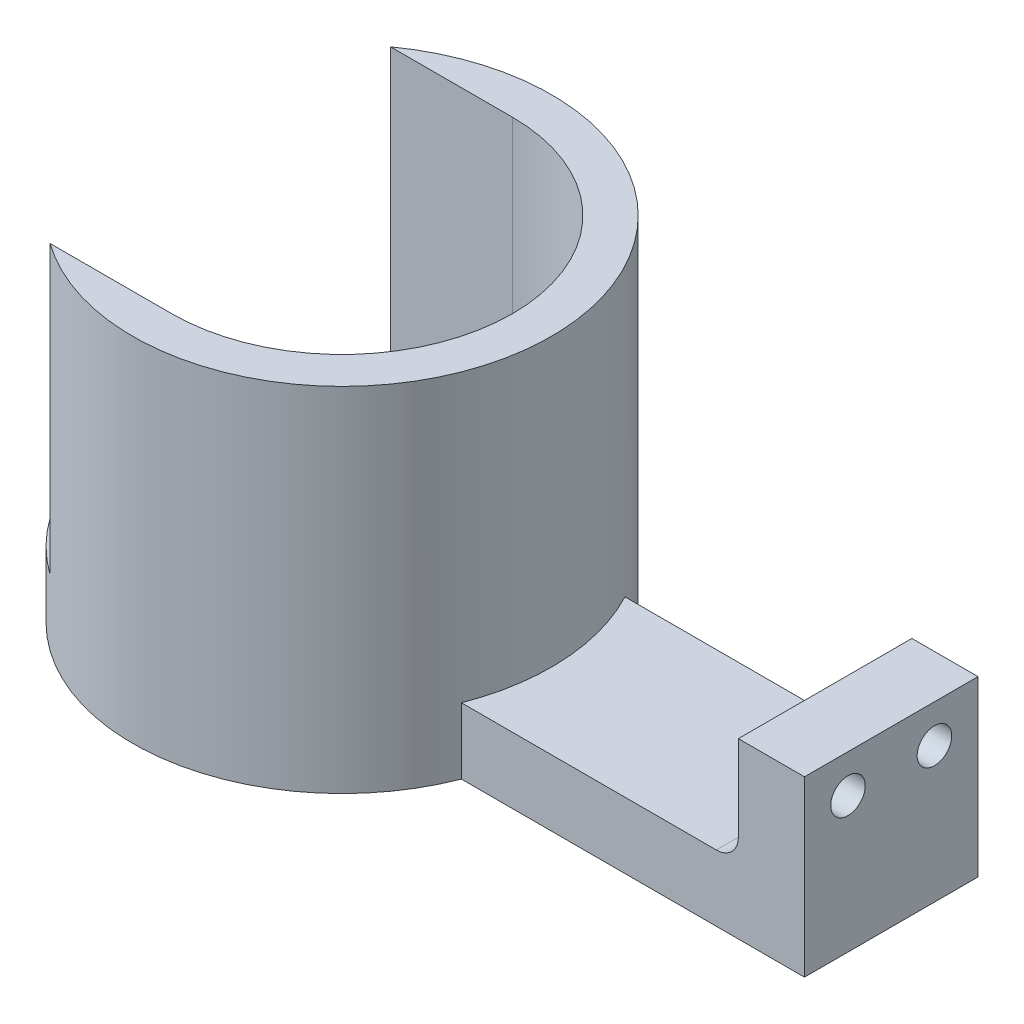
SolidWorks part; units mm, degrees
ref_plane "Front Plane" through (0, 0, 0) normal (0, 0, 1) x (1, 0, 0)
ref_plane "Top Plane" through (0, 0, 0) normal (0, 1, 0) x (1, 0, 0)
ref_plane "Right Plane" through (0, 0, 0) normal (1, 0, 0) x (0, 0, -1)
sketch "Sketch1" plane through (0, 0, 0) normal (0, 1, 0) x (1, 0, 0)
  line L1 (42.6873, 22.5127) -> (124.0573, 22.5127)
  line L2 (42.6873, 22.5127) -> (42.6873, -17.4873)
  line L3 (42.6873, -17.4873) -> (124.0573, -17.4873)
  line L4 (124.0573, 22.5127) -> (124.0573, -17.4873)
  circle A0 centre (0, 0) radius 26.5621
  circle A2 centre (0, 0) radius 48.26
  dimension "D1" = 53.1241
  dimension "D4" = 96.52
  dimension "D2" = 81.37
  dimension "D3" = 40
extrude "Boss-Extrude2" add sketch "Sketch1" along normal blind 15.24 contours L2 A2 A0 | A2 L3 L4 L1 | L2 A2
sketch "Sketch2" plane through (0, 0, -22.5127) normal (0, 0, -1) x (-1, 0, 0)
  line L1 (-124.0573, 15.24) -> (-108.8173, 15.24)
  line L2 (-124.0573, 15.24) -> (-124.0573, 40)
  line L3 (-124.0573, 40) -> (-108.8173, 40)
  line L4 (-108.8173, 15.24) -> (-108.8173, 40)
  dimension "D1" = 15.24
extrude "Boss-Extrude3" add sketch "Sketch2" against normal up to surface (40 mm away) up to face at (84.5188, 7.62, 17.4873)
sketch "Sketch3" plane through (108.8173, 0, 0) normal (-1, 0, 0) x (0, 0, 1)
  line L0 (-22.5127, 15.24) -> (-22.5127, 40) construction
  line L1 (17.4873, 40) -> (-22.5127, 40) construction
  line L2 (17.4873, 40) -> (17.4873, 15.24) construction
  circle A0 centre (7.4492, 31.2218) radius 3.9774
  circle A1 centre (-12.4746, 31.2218) radius 3.9851
  dimension "D1" = 7.9547
  dimension "D2" = 7.9703
  dimension "D3" = 10.0381
  dimension "D4" = 8.7782
  dimension "D5" = 8.7782
  dimension "D6" = 10.0381
extrude "Cut-Extrude1" cut sketch "Sketch3" against normal through all
fillet "Fillet1" radius 5.08 1 edges at (108.8173, 15.24, -2.5127)
sketch "Sketch5" plane through (0, 15.24, 0) normal (0, 1, 0) x (1, 0, 0)
  line L0 (0, -39.2481) -> (-28.0822, -39.2481)
  line L1 (0, 39.2481) -> (-28.0822, 39.2481)
  arc A0 (0, -39.2481) -> (0, 39.2481) centre (0, 0) ccw
  arc A1 (42.6873, 22.5127) -> (44.9802, -17.4873) centre (0, 0) ccw construction
  circle A2 centre (0, 0) radius 48.26
  point P9 (0, 0)
  point P11 (0, 0)
  point P12 (0, 0)
  point P13 (-28.6493, 38.8361)
  point P14 (0, 0)
  point P15 (0, 0)
  point P16 (-28.4341, 38.994)
  point P17 (-29.4505, -38.2321)
  point P18 (0, 0)
  point P19 (0, 0)
  point P20 (0, 0)
  point P21 (0, 0)
  arc M5 (42.6873, 22.5127) -> (44.9802, -17.4873) centre (0, 0) ccw
extrude "Boss-Extrude4" add sketch "Sketch5" along normal blind 66.04 contours A2 L1 A0 L0 M5
